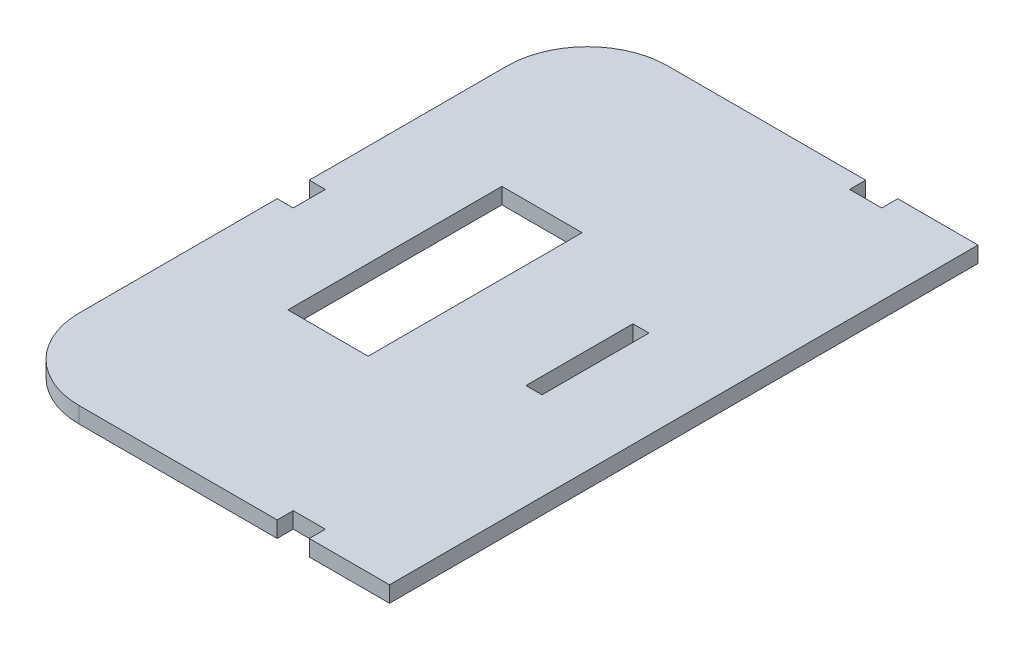
SolidWorks part; units mm, degrees
ref_plane "Спереди" through (0, 0, 0) normal (0, 0, 1) x (1, 0, 0)
ref_plane "Сверху" through (0, 0, 0) normal (0, 1, 0) x (1, 0, 0)
ref_plane "Справа" through (0, 0, 0) normal (1, 0, 0) x (0, 0, -1)
other "Configuration Table"
sketch "Эскиз4" plane through (0, 0, 0) normal (0, 1, 0) x (1, 0, 0)
  line L0 (0, 58) -> (0, 110)
  line L1 (0, 0) -> (52, 0)
  line L2 (0, 0) -> (0, 52)
  line L3 (0, 110) -> (52, 110)
  line L6 (55, 107) -> (52, 107)
  line L7 (52, 107) -> (55, 107)
  line L8 (55, 107) -> (58, 107)
  line L9 (52, 107) -> (52, 110)
  line L10 (58, 107) -> (58, 110)
  line L11 (58, 3) -> (58, 0)
  line L12 (55, 3) -> (58, 3)
  line L13 (55, 3) -> (52, 3)
  line L14 (52, 3) -> (52, 0)
  line L15 (3, 55) -> (3, 58)
  line L16 (3, 55) -> (3, 52)
  line L17 (3, 58) -> (0, 58)
  line L18 (3, 52) -> (0, 52)
  line L22 (58, 0) -> (73, 0)
  line L24 (58, 110) -> (73, 110)
  line L25 (55, 107) -> (55, 3) construction
  line L26 (3, 55) -> (73, 55)
  line L27 (73, 110) -> (73, 0)
  dimension "D1" = 3
  dimension "D2" = 3
  dimension "D3" = 3
  dimension "D4" = 15
  dimension "D5" = 3
  dimension "D6" = 3
  dimension "D7" = 3
extrude "Бобышка-Вытянуть3" add sketch "Эскиз4" along normal blind 3
sketch "Sketch1" plane through (0, 3, 0) normal (0, 1, 0) x (1, 0, 0)
  line L0 (3, 52) -> (3, 58) construction
  line L13 (3, 55) -> (107, 55) construction
  line L15 (55, 107) -> (55, 3) construction
  line L16 (52, 107) -> (58, 107) construction
  line L17 (58, 3) -> (52, 3) construction
  line L19 (19, 75) -> (34, 75)
  line L20 (19, 75) -> (19, 35)
  line L21 (19, 35) -> (34, 35)
  line L22 (34, 75) -> (34, 35)
  line L23 (53.5, 65) -> (56.5, 65)
  line L24 (53.5, 65) -> (53.5, 45)
  line L25 (53.5, 45) -> (56.5, 45)
  line L26 (56.5, 65) -> (56.5, 45)
  dimension "D1" = 3
  dimension "D2" = 20
  dimension "D3" = 16
  dimension "D4" = 15
  dimension "D5" = 40
extrude "Cut-Extrude1" cut sketch "Sketch1" against normal blind 10
fillet "Fillet1" radius 15 2 edges at (0, 1.5, 0) (0, 1.5, -110)
